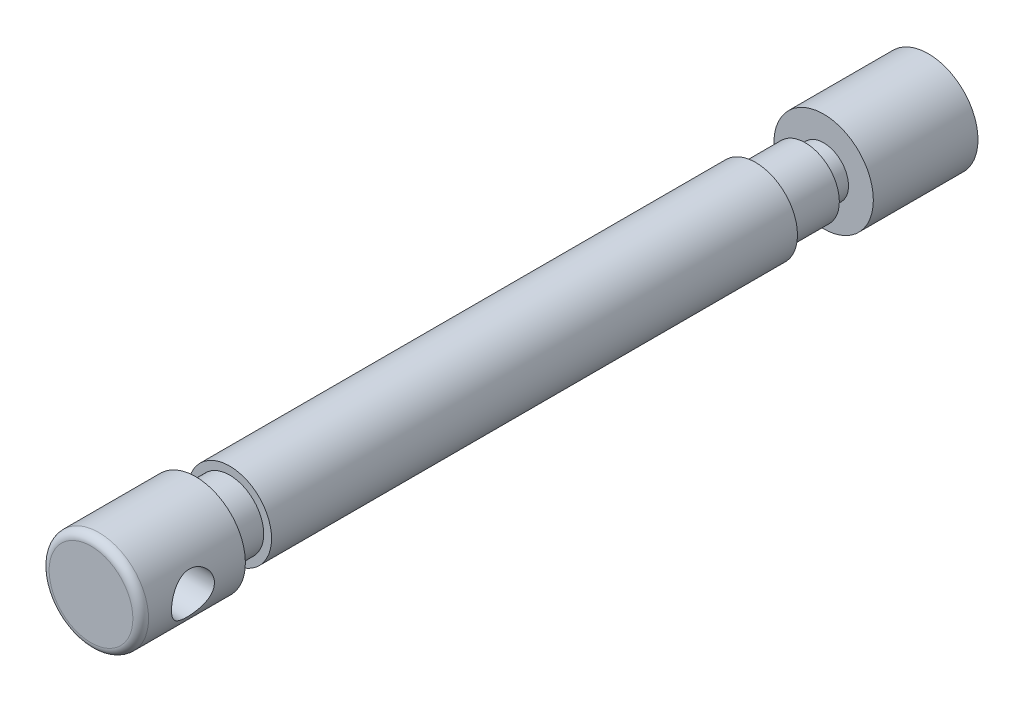
SolidWorks part; units mm, degrees
ref_plane "Front Plane" through (0, 0, 0) normal (0, 0, 1) x (1, 0, 0)
ref_plane "Top Plane" through (0, 0, 0) normal (0, 1, 0) x (1, 0, 0)
ref_plane "Right Plane" through (0, 0, 0) normal (1, 0, 0) x (0, 0, -1)
sketch "Sketch1" plane through (0, 0, 0) normal (0, 0, 1) x (1, 0, 0)
  circle A0 centre (0, 0) radius 9.5
  dimension "D1" = 19
extrude "Boss-Extrude1" add sketch "Sketch1" along normal blind 20
sketch "Sketch2" plane through (0, 0, 20) normal (0, 0, 1) x (1, 0, 0)
  circle A0 centre (0, 0) radius 4.75
  dimension "D1" = 9.5
extrude "Boss-Extrude2" add sketch "Sketch2" along normal blind 3.5
sketch "Sketch3" plane through (0, 0, 23.5) normal (0, 0, 1) x (1, 0, 0)
  circle A0 centre (0, 0) radius 6.5
  dimension "D1" = 13
extrude "Boss-Extrude3" add sketch "Sketch3" along normal blind 9.5
sketch "Sketch4" plane through (0, 0, 33) normal (0, 0, 1) x (1, 0, 0)
  circle A0 centre (0, 0) radius 8
  dimension "D1" = 16
extrude "Boss-Extrude4" add sketch "Sketch4" along normal blind 100.5
sketch "Sketch5" plane through (0, 0, 133.5) normal (0, 0, 1) x (1, 0, 0)
  circle A0 centre (0, 0) radius 6.5
  dimension "D1" = 13
extrude "Boss-Extrude5" add sketch "Sketch5" along normal blind 6.5
sketch "Sketch6" plane through (0, 0, 140) normal (0, 0, 1) x (1, 0, 0)
  circle A0 centre (0, 0) radius 9.5
  dimension "D1" = 19
extrude "Boss-Extrude6" add sketch "Sketch6" along normal blind 20
sketch "Sketch7" plane through (0, 0, 0) normal (1, 0, 0) x (0, 0, -1)
  line L0 (-160, 9.5) -> (-160, -9.5) construction
  line L1 (-140, 9.5) -> (-160, 9.5) construction
  circle A0 centre (-150, -0.5) radius 4.1
  dimension "D1" = 8.2
  dimension "D2" = 10
  dimension "D3" = 10
extrude "Cut-Extrude1" cut sketch "Sketch7" against normal through all both and the other way through all
fillet "Fillet1" radius 1.5 1 edges at (9.5, 0, 160)
